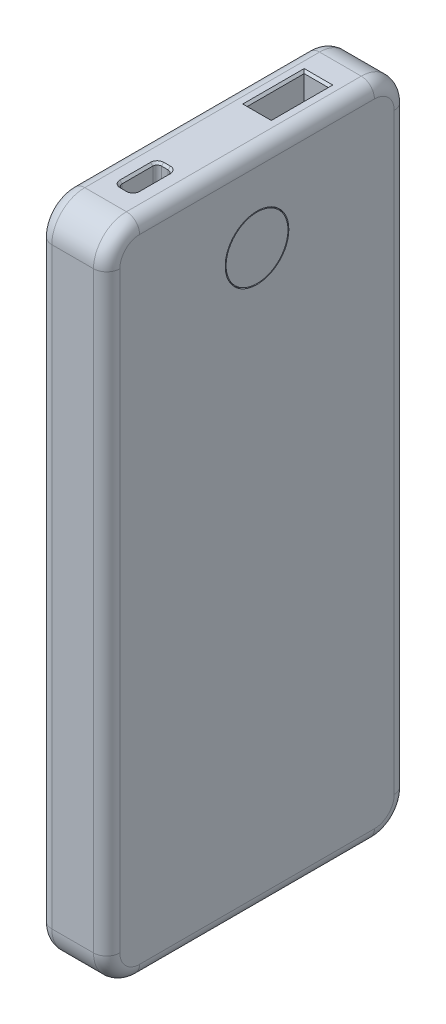
SolidWorks part; units mm, degrees
ref_plane "正面" through (0, 0, 0) normal (0, 0, 1) x (1, 0, 0)
ref_plane "平面" through (0, 0, 0) normal (0, 1, 0) x (1, 0, 0)
ref_plane "右側面" through (0, 0, 0) normal (1, 0, 0) x (0, 0, -1)
sketch "ｽｹｯﾁ1" plane through (0, 0, 0) normal (0, 1, 0) x (1, 0, 0)
  line L1 (-7.75, 34.25) -> (7.75, 34.25)
  line L2 (-7.75, 34.25) -> (-7.75, -34.25)
  line L3 (-7.75, -34.25) -> (7.75, -34.25)
  line L4 (7.75, 34.25) -> (7.75, -34.25)
  line L5 (-7.75, 34.25) -> (7.75, -34.25) construction
  line L6 (-7.75, -34.25) -> (7.75, 34.25) construction
  point P0 (0, 0)
  dimension "D1" = 15.5
  dimension "D2" = 68.5
extrude "ﾎﾞｽ - 押し出し1" add sketch "ｽｹｯﾁ1" along normal blind 150
sketch "ｽｹｯﾁ2" plane through (0, 150, 0) normal (0, 1, 0) x (1, 0, 0)
  line L0 (0, 0) -> (0, 34.25) construction
  line L1 (7.75, 34.25) -> (-7.75, 34.25) construction
  line L2 (0, 0) -> (0, -34.25) construction
  line L3 (-2.75, 21.25) -> (2.75, 21.25)
  line L4 (-2.75, 21.25) -> (-2.75, 8.25)
  line L5 (-2.75, 8.25) -> (2.75, 8.25)
  line L6 (2.75, 21.25) -> (2.75, 8.25)
  line L7 (-2.75, 21.25) -> (2.75, 8.25) construction
  line L8 (-2.75, 8.25) -> (2.75, 21.25) construction
  line L9 (-7.75, -34.25) -> (7.75, -34.25) construction
  line L11 (-0.75, -13.25) -> (0.75, -13.25)
  line L12 (-1.75, -14.25) -> (-1.75, -21.25)
  line L13 (-0.75, -22.25) -> (0.75, -22.25)
  line L14 (1.75, -14.25) -> (1.75, -21.25)
  line L15 (-1.75, -13.25) -> (1.75, -22.25) construction
  line L16 (-1.75, -22.25) -> (1.75, -13.25) construction
  arc A0 (0.75, -22.25) -> (1.75, -21.25) centre (0.75, -21.25) ccw
  arc A1 (-1.75, -21.25) -> (-0.75, -22.25) centre (-0.75, -21.25) ccw
  arc A2 (0.75, -13.25) -> (1.75, -14.25) centre (0.75, -14.25) cw
  arc A3 (-0.75, -13.25) -> (-1.75, -14.25) centre (-0.75, -14.25) ccw
  point P5 (0, 14.75)
  point P13 (0, -17.75)
  point P18 (0, -22.25)
  dimension "D7" = 1
  dimension "D1" = 5.5
  dimension "D2" = 13
  dimension "D3" = 13
  dimension "D4" = 9
  dimension "D5" = 3.5
  dimension "D6" = 12
extrude "ｶｯﾄ - 押し出し1" cut sketch "ｽｹｯﾁ2" against normal blind 10
chamfer "面取り1" distance 0.5 angle 45 12 edges at (1.75, 150, 17.75) (1.4571, 150, 13.5429) (1.4571, 150, 21.9571) (0, 150, 13.25) (0, 150, 22.25) (-1.4571, 150, 13.5429) (-1.4571, 150, 21.9571) (-1.75, 150, 17.75) (0, 150, -8.25) (-2.75, 150, -14.75) (2.75, 150, -14.75) (0, 150, -21.25)
fillet "ﾌｨﾚｯﾄ1" radius 7.5 4 edges at (0, 0, -34.25) (0, 0, 34.25) (0, 150, -34.25) (0, 150, 34.25)
fillet "ﾌｨﾚｯﾄ2" radius 3 16 edges at (-7.75, 147.8033, -32.0533) (-7.75, 75, -34.25) (-7.75, 2.1967, -32.0533) (-7.75, 0, 0) (-7.75, 2.1967, 32.0533) (-7.75, 75, 34.25) (-7.75, 147.8033, 32.0533) (7.75, 147.8033, 32.0533) (7.75, 75, 34.25) (7.75, 2.1967, 32.0533) (7.75, 0, 0) (7.75, 2.1967, -32.0533) (7.75, 75, -34.25) (7.75, 147.8033, -32.0533) (-7.75, 150, 0) (7.75, 150, 0)
sketch "ｽｹｯﾁ3" plane through (7.75, 0, 0) normal (1, 0, 0) x (0, 0, -1)
  line L0 (0, 150) -> (0, 131) construction
  line L1 (-26.75, 150) -> (26.75, 150) construction
  circle A0 centre (0, 131) radius 7.25
  circle A1 centre (0, 131) radius 7.05
  dimension "D1" = 14.5
  dimension "D2" = 19
  dimension "D3" = 0.2
extrude "ｶｯﾄ - 押し出し2" cut sketch "ｽｹｯﾁ3" against normal blind 0.5
